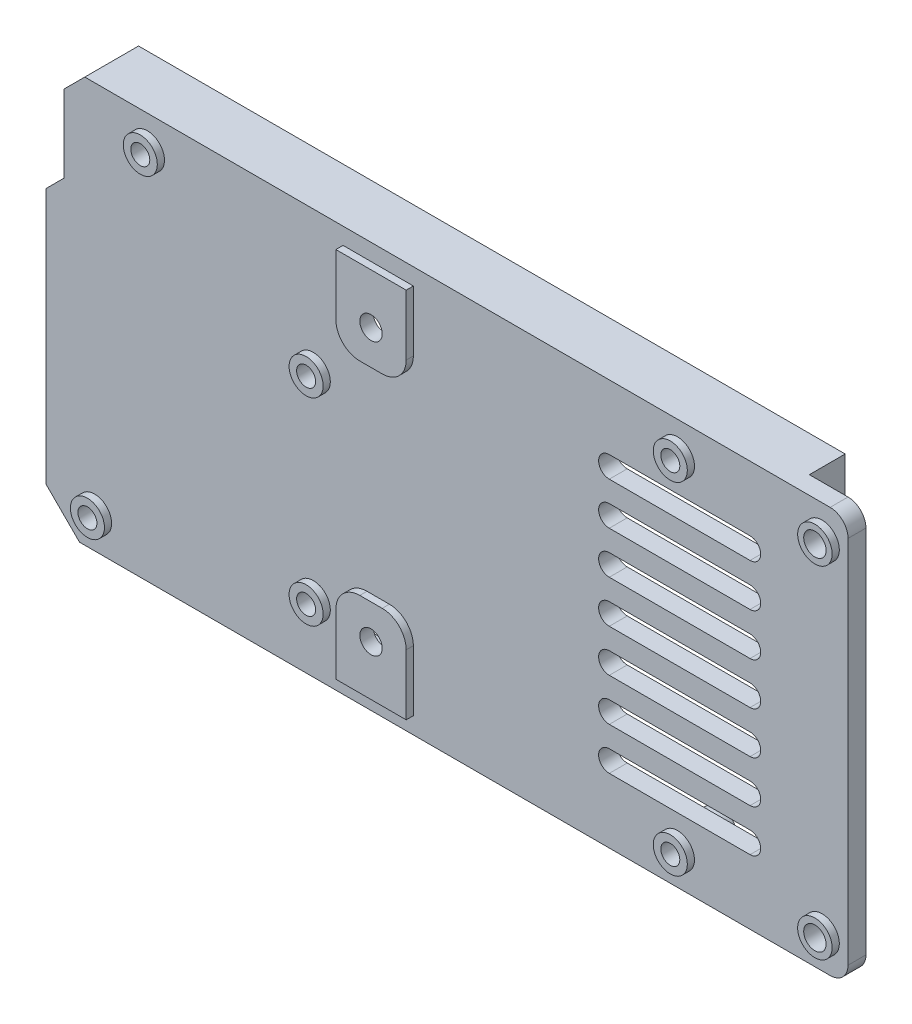
SolidWorks part; units mm, degrees
material "ABS PC"
ref_plane "Front Plane" through (0, 0, 0) normal (0, 0, 1) x (1, 0, 0)
ref_plane "Top Plane" through (0, 0, 0) normal (0, 1, 0) x (1, 0, 0)
ref_plane "Right Plane" through (0, 0, 0) normal (1, 0, 0) x (0, 0, -1)
sketch "Sketch1" plane through (0, 0, -0.0381) normal (0, 0, 1) x (1, 0, 0)
  line L24 (-48.26, 14.0081) -> (-50.8, 11.4681)
  line L25 (-50.8, 11.4681) -> (-50.8, -23.1521)
  line L26 (-50.8, -23.1521) -> (-47.244, -26.7081)
  line L27 (-47.244, -26.7081) -> (49.276, -26.7081)
  line L28 (49.276, -26.7081) -> (50.8, -25.1841)
  line L29 (50.8, -25.1841) -> (50.8, 25.1841)
  line L30 (50.8, 25.1841) -> (49.276, 26.7081)
  line L31 (49.276, 26.7081) -> (-46.4966, 26.7081)
  line L32 (-46.4966, 26.7081) -> (-48.26, 24.9447)
  line L33 (-48.26, 24.9447) -> (-48.26, 14.0081)
  circle A8 centre (36.6776, -24.1681) radius 1.5621
  circle A9 centre (-45.9486, -24.1681) radius 1.5621
  circle A10 centre (-14.9479, -19.2896) radius 1.5621
  circle A11 centre (-38.4556, 24.1681) radius 1.5621
  circle A12 centre (-14.9479, 8.7266) radius 1.3153
  circle A13 centre (36.6776, 24.1681) radius 1.5621
  dimension "D1" = 2.6305
  dimension "D2" = 3.1242
  dimension "D3" = 36.6776
  dimension "D4" = 49.276
  dimension "D5" = 50.8
  dimension "D6" = 14.9479
  dimension "D7" = 38.4556
  dimension "D8" = 45.9486
  dimension "D9" = 46.4966
  dimension "D10" = 47.244
  dimension "D11" = 48.26
  dimension "D12" = 50.8
  dimension "D13" = 8.7266
  dimension "D14" = 11.4681
  dimension "D15" = 24.9447
  dimension "D16" = 24.1681
  dimension "D17" = 23.1521
  dimension "D20" = 19.2896
  dimension "D22" = 24.1681
sketch "Sketch2" plane through (0, 0, 0) normal (0, 0, 1) x (1, 0, 0)
  line L0 (49.276, 26.7081) -> (-46.4966, 26.7081) construction
  line L1 (-46.4966, 26.7081) -> (-48.26, 24.9447) construction
  line L2 (-48.26, 24.9447) -> (-48.26, 14.0081) construction
  line L3 (-48.26, 14.0081) -> (-50.8, 11.4681) construction
  line L4 (-50.8, 11.4681) -> (-50.8, -23.1521) construction
  line L5 (-50.8, -23.1521) -> (-47.244, -26.7081) construction
  line L6 (-47.244, -26.7081) -> (49.276, -26.7081) construction
  line L8 (50.8, -25.1841) -> (50.8, 25.1841) construction
  line L10 (50.8, 26.7081) -> (-46.4966, 26.7081)
  line L11 (-46.4966, 26.7081) -> (-48.26, 24.9447)
  line L12 (-48.26, 24.9447) -> (-48.26, 14.0081)
  line L13 (-48.26, 14.0081) -> (-50.8, 11.4681)
  line L14 (-50.8, 11.4681) -> (-50.8, -23.1521)
  line L15 (-50.8, -23.1521) -> (-47.244, -26.7081)
  line L16 (-47.244, -26.7081) -> (50.8, -26.7081)
  line L18 (50.8, -26.7081) -> (50.8, 26.7081)
  line L20 (52.832, 28.7401) -> (-47.3382, 28.7401)
  line L21 (-47.3382, 28.7401) -> (-50.292, 25.7863)
  line L22 (-50.292, 25.7863) -> (-50.292, 14.8498)
  line L23 (-50.292, 14.8498) -> (-52.832, 12.3098)
  line L24 (-52.832, 12.3098) -> (-52.832, -23.9938)
  line L25 (-52.832, -23.9938) -> (-48.0857, -28.7401)
  line L26 (-48.0857, -28.7401) -> (52.832, -28.7401)
  line L28 (52.832, -28.7401) -> (52.832, 28.7401)
  line L30 (49.276, -26.7081) -> (50.8, -25.1841) construction
  line L31 (50.1177, -28.7401) -> (52.832, -26.0258) construction
  line L32 (52.832, 26.0258) -> (50.1177, 28.7401) construction
  line L33 (50.8, 25.1841) -> (49.276, 26.7081) construction
  line L34 (50.8, -25.1841) -> (50.8, 25.1841) construction
  line L35 (49.276, 26.7081) -> (-46.4966, 26.7081) construction
  line L36 (50.1177, 28.7401) -> (-47.3382, 28.7401) construction
  line L37 (52.832, -26.0258) -> (52.832, 26.0258) construction
  line L38 (-47.244, -26.7081) -> (49.276, -26.7081) construction
  line L39 (-48.0857, -28.7401) -> (50.1177, -28.7401) construction
  dimension "D1" = 2.032
extrude "Boss-Extrude2" add sketch "Sketch2" along normal blind 5.08
sketch "Sketch3" plane through (0, 0, 5.08) normal (0, 0, 1) x (1, 0, 0)
  line L0 (-48.0857, -28.7401) -> (52.832, -28.7401) construction
  line L1 (-52.832, -23.9938) -> (-48.0857, -28.7401) construction
  line L2 (-52.832, 12.3098) -> (-52.832, -23.9938) construction
  line L3 (-50.292, 14.8498) -> (-52.832, 12.3098) construction
  line L4 (-50.292, 25.7863) -> (-50.292, 14.8498) construction
  line L5 (-47.3382, 28.7401) -> (-50.292, 25.7863) construction
  line L6 (52.832, 28.7401) -> (-47.3382, 28.7401) construction
  line L7 (-48.0857, -28.7401) -> (60.8584, -28.7401)
  line L8 (-52.832, -23.9938) -> (-48.0857, -28.7401)
  line L9 (-52.832, 12.3098) -> (-52.832, -23.9938)
  line L10 (-50.292, 14.8498) -> (-52.832, 12.3098)
  line L11 (-50.292, 25.7863) -> (-50.292, 14.8498)
  line L12 (-47.3382, 28.7401) -> (-50.292, 25.7863)
  line L13 (60.8584, 28.7401) -> (-47.3382, 28.7401)
  line L14 (60.8584, 28.7401) -> (60.8584, -28.7401)
  circle A0 centre (57.1754, 24.1681) radius 1.5875
  circle A1 centre (57.1754, -24.1681) radius 1.5875
  circle A2 centre (36.6776, 24.1681) radius 1.3462
  circle A3 centre (-38.4556, 24.1681) radius 1.3462
  circle A4 centre (-14.9479, 8.7266) radius 1.3462
  circle A5 centre (-14.9479, -19.2896) radius 1.3462
  circle A6 centre (-45.9486, -24.1681) radius 1.3462
  circle A7 centre (36.6776, -24.1681) radius 1.3462
  point P32 (0, 0)
  point P33 (0, 0)
  point P34 (0, 0)
  dimension "D2" = 2.6924
  dimension "D3" = 3.175
  dimension "D1" = 113.6904
  dimension "D4" = 3.683
extrude "Boss-Extrude3" add sketch "Sketch3" along normal blind 2.54
sketch "Sketch4" plane through (0, 0, 5.08) normal (0, 0, -1) x (-1, 0, 0)
  line L0 (-39.0906, 24.1681) -> (-39.0906, 26.7081)
  line L1 (-50.8, 26.7081) -> (46.4966, 26.7081) construction
  line L2 (-39.0906, 26.7081) -> (-34.2646, 26.7081)
  line L3 (-34.2646, 26.7081) -> (-34.2646, 24.1681)
  line L4 (36.0426, 24.1681) -> (36.0426, 26.7081)
  line L5 (36.0426, 26.7081) -> (40.8686, 26.7081)
  line L6 (-50.8, 26.7081) -> (46.4966, 26.7081) construction
  line L7 (40.8686, 26.7081) -> (40.8686, 24.1681)
  line L8 (48.3616, -24.1681) -> (49.784, -24.1681)
  line L9 (50.8, -23.1521) -> (47.244, -26.7081) construction
  line L10 (49.784, -24.1681) -> (47.244, -26.7081)
  line L11 (47.244, -26.7081) -> (43.5356, -26.7081)
  line L12 (47.244, -26.7081) -> (-50.8, -26.7081) construction
  line L13 (43.5356, -26.7081) -> (43.5356, -24.1681)
  line L14 (-39.0906, -24.1681) -> (-39.0906, -26.7081)
  line L15 (-39.0906, -26.7081) -> (-34.2646, -26.7081)
  line L16 (47.244, -26.7081) -> (-50.8, -26.7081) construction
  line L17 (-34.2646, -26.7081) -> (-34.2646, -24.1681)
  arc A0 (36.0426, 24.1681) -> (40.8686, 24.1681) centre (38.4556, 24.1681) ccw
  circle A1 centre (14.9479, 8.7266) radius 2.413
  circle A2 centre (14.9479, -19.2896) radius 2.413
  arc A3 (48.3616, -24.1681) -> (43.5356, -24.1681) centre (45.9486, -24.1681) ccw
  arc A4 (-34.2646, -24.1681) -> (-39.0906, -24.1681) centre (-36.6776, -24.1681) ccw
  arc A5 (-39.0906, 24.1681) -> (-34.2646, 24.1681) centre (-36.6776, 24.1681) ccw
  circle A6 centre (45.9486, -24.1681) radius 1.3462 construction
  circle A7 centre (14.9479, -19.2896) radius 1.3462 construction
  circle A8 centre (-36.6776, -24.1681) radius 1.3462 construction
  circle A9 centre (14.9479, 8.7266) radius 1.3462 construction
  circle A10 centre (38.4556, 24.1681) radius 1.3462 construction
  circle A11 centre (-36.6776, 24.1681) radius 1.3462 construction
  circle A12 centre (45.9486, -24.1681) radius 1.3462
  circle A13 centre (14.9479, -19.2896) radius 1.3462
  circle A14 centre (-36.6776, -24.1681) radius 1.3462
  circle A15 centre (14.9479, 8.7266) radius 1.3462
  circle A16 centre (38.4556, 24.1681) radius 1.3462
  circle A17 centre (-36.6776, 24.1681) radius 1.3462
  dimension "D1" = 4.826
  dimension "D2" = 4.826
extrude "Boss-Extrude4" add sketch "Sketch4" along normal blind 3.4671
sketch "Sketch5" plane through (0, 0, 5.08) normal (0, 0, -1) x (-1, 0, 0)
  line L0 (-46.9646, 18.0594) -> (-27.0129, 18.0594) construction
  line L1 (-46.9646, 19.5707) -> (-27.0129, 19.5707)
  line L2 (-46.9646, 16.5481) -> (-27.0129, 16.5481)
  line L3 (-50.8, -26.7081) -> (-50.8, 26.7081) construction
  line L4 (-50.8, 26.7081) -> (46.4966, 26.7081) construction
  line L5 (-46.9646, 12.0396) -> (-27.0129, 12.0396) construction
  line L6 (-46.9646, 13.5509) -> (-27.0129, 13.5509)
  line L7 (-46.9646, 10.5283) -> (-27.0129, 10.5283)
  line L8 (-46.9646, 6.0198) -> (-27.0129, 6.0198) construction
  line L9 (-46.9646, 7.5311) -> (-27.0129, 7.5311)
  line L10 (-46.9646, 4.5085) -> (-27.0129, 4.5085)
  line L11 (-46.9646, 0) -> (-27.0129, 0) construction
  line L12 (-46.9646, 1.5113) -> (-27.0129, 1.5113)
  line L13 (-46.9646, -1.5113) -> (-27.0129, -1.5113)
  line L14 (-46.9646, -6.0198) -> (-27.0129, -6.0198) construction
  line L15 (-46.9646, -4.5085) -> (-27.0129, -4.5085)
  line L16 (-46.9646, -7.5311) -> (-27.0129, -7.5311)
  line L17 (-46.9646, -12.0396) -> (-27.0129, -12.0396) construction
  line L18 (-46.9646, -10.5283) -> (-27.0129, -10.5283)
  line L19 (-46.9646, -13.5509) -> (-27.0129, -13.5509)
  line L20 (-46.9646, -18.0594) -> (-27.0129, -18.0594) construction
  line L21 (-46.9646, -16.5481) -> (-27.0129, -16.5481)
  line L22 (-46.9646, -19.5707) -> (-27.0129, -19.5707)
  line L23 (47.244, -26.7081) -> (-50.8, -26.7081) construction
  arc A0 (-46.9646, 19.5707) -> (-46.9646, 16.5481) centre (-46.9646, 18.0594) ccw
  arc A1 (-27.0129, 16.5481) -> (-27.0129, 19.5707) centre (-27.0129, 18.0594) ccw
  arc A2 (-46.9646, 13.5509) -> (-46.9646, 10.5283) centre (-46.9646, 12.0396) ccw
  arc A3 (-27.0129, 10.5283) -> (-27.0129, 13.5509) centre (-27.0129, 12.0396) ccw
  arc A4 (-46.9646, 7.5311) -> (-46.9646, 4.5085) centre (-46.9646, 6.0198) ccw
  arc A5 (-27.0129, 4.5085) -> (-27.0129, 7.5311) centre (-27.0129, 6.0198) ccw
  arc A6 (-46.9646, 1.5113) -> (-46.9646, -1.5113) centre (-46.9646, 0) ccw
  arc A7 (-27.0129, -1.5113) -> (-27.0129, 1.5113) centre (-27.0129, 0) ccw
  arc A8 (-46.9646, -4.5085) -> (-46.9646, -7.5311) centre (-46.9646, -6.0198) ccw
  arc A9 (-27.0129, -7.5311) -> (-27.0129, -4.5085) centre (-27.0129, -6.0198) ccw
  arc A10 (-46.9646, -10.5283) -> (-46.9646, -13.5509) centre (-46.9646, -12.0396) ccw
  arc A11 (-27.0129, -13.5509) -> (-27.0129, -10.5283) centre (-27.0129, -12.0396) ccw
  arc A12 (-46.9646, -16.5481) -> (-46.9646, -19.5707) centre (-46.9646, -18.0594) ccw
  arc A13 (-27.0129, -19.5707) -> (-27.0129, -16.5481) centre (-27.0129, -18.0594) ccw
  point P2 (-36.9887, 18.0594)
  point P7 (-48.4759, 18.0594)
  point P8 (-25.5016, 18.0594)
  point P16 (-36.9887, 12.0396)
  point P23 (-36.9887, 6.0198)
  point P30 (-36.9887, 0)
  point P37 (-36.9887, -6.0198)
  point P44 (-36.9887, -12.0396)
  point P51 (-36.9887, -18.0594)
  dimension "D1" = 3.0226
  dimension "D2" = 22.9743
  dimension "D3" = 25.2984
  dimension "D4" = 10.16
  dimension "D6" = 10.16
  dimension "D5" = 7
extrude "Cut-Extrude1" cut sketch "Sketch5" against normal up to next
sketch "Sketch6" plane through (0, 0, 7.62) normal (0, 0, 1) x (1, 0, 0)
  line L0 (-7.3343, -14.3891) -> (-4.1593, -14.3891)
  line L1 (-0.762, -17.7864) -> (-0.762, -26.3779)
  line L2 (-0.762, -26.3779) -> (-10.7315, -26.3779)
  line L3 (-10.7315, -26.3779) -> (-10.7315, -17.7864)
  line L4 (-52.832, 12.3098) -> (-52.832, -23.9938) construction
  line L5 (-48.0857, -28.7401) -> (60.8584, -28.7401) construction
  line L6 (-5.7468, -14.3891) -> (-5.7468, -22.939) construction
  line L7 (0, 0) -> (-25.6269, 0) construction
  line L8 (-5.7468, 14.3891) -> (-5.7468, 22.939) construction
  line L9 (-10.7315, 26.3779) -> (-10.7315, 17.7864)
  line L10 (-0.762, 26.3779) -> (-10.7315, 26.3779)
  line L11 (-0.762, 17.7864) -> (-0.762, 26.3779)
  line L12 (-7.3343, 14.3891) -> (-4.1593, 14.3891)
  circle A0 centre (-14.9479, -19.2896) radius 2.413 construction
  circle A1 centre (-14.9479, 8.7266) radius 2.413 construction
  circle A2 centre (57.1754, -24.1681) radius 1.5875 construction
  circle A3 centre (57.1754, 24.1681) radius 1.5875 construction
  circle A4 centre (36.6776, -24.1681) radius 1.3462 construction
  circle A5 centre (36.6776, 24.1681) radius 1.3462 construction
  circle A6 centre (-14.9479, -19.2896) radius 1.3462 construction
  circle A7 centre (-14.9479, 8.7266) radius 1.3462 construction
  circle A8 centre (-38.4556, 24.1681) radius 1.3462 construction
  circle A9 centre (-45.9486, -24.1681) radius 1.3462 construction
  circle A10 centre (-14.9479, -19.2896) radius 2.413
  circle A11 centre (-14.9479, 8.7266) radius 2.413
  circle A12 centre (57.1754, -24.1681) radius 1.5875
  circle A13 centre (57.1754, 24.1681) radius 1.5875
  circle A14 centre (36.6776, -24.1681) radius 1.3462
  circle A15 centre (36.6776, 24.1681) radius 1.3462
  circle A16 centre (-14.9479, -19.2896) radius 1.3462
  circle A17 centre (-14.9479, 8.7266) radius 1.3462
  circle A18 centre (-38.4556, 24.1681) radius 1.3462
  circle A19 centre (-45.9486, -24.1681) radius 1.3462
  circle A20 centre (-45.9486, -24.1681) radius 2.413
  circle A21 centre (-38.4556, 24.1681) radius 2.413
  circle A22 centre (36.6776, 24.1681) radius 2.413
  circle A23 centre (36.6776, -24.1681) radius 2.413
  circle A24 centre (57.1754, 24.1681) radius 2.4448
  circle A25 centre (57.1754, -24.1681) radius 2.4448
  arc A26 (-4.1593, -14.3891) -> (-0.762, -17.7864) centre (-4.1593, -17.7864) cw
  arc A27 (-10.7315, -17.7864) -> (-7.3343, -14.3891) centre (-7.3343, -17.7864) cw
  circle A28 centre (-5.7468, -19.2896) radius 1.5875
  circle A29 centre (-5.7468, 19.2896) radius 1.5875
  arc A30 (-10.7315, 17.7864) -> (-7.3343, 14.3891) centre (-7.3343, 17.7864) ccw
  arc A31 (-4.1593, 14.3891) -> (-0.762, 17.7864) centre (-4.1593, 17.7864) ccw
  dimension "D1" = 4.8895
  dimension "D2" = 11.9888
  dimension "D4" = 3.175
  dimension "D3" = 9.9695
  dimension "D5" = 52.07
  dimension "D6" = 14.351
extrude "Boss-Extrude5" add sketch "Sketch6" along normal blind 1.016
sketch "Sketch8" plane through (0, 0, 5.08) normal (0, 0, -1) x (-1, 0, 0)
  line L8 (9.8425, 17.7864) -> (9.8425, 25.4889)
  line L9 (4.1593, 15.2781) -> (7.3343, 15.2781)
  line L10 (1.651, 25.4889) -> (1.651, 17.7864)
  line L11 (9.8425, 25.4889) -> (1.651, 25.4889)
  line L12 (9.8425, 17.7864) -> (9.8425, 25.4889)
  line L13 (4.1593, 15.2781) -> (7.3343, 15.2781)
  line L14 (1.651, 25.4889) -> (1.651, 17.7864)
  line L15 (9.8425, 25.4889) -> (1.651, 25.4889)
  line L20 (1.651, -25.4889) -> (9.8425, -25.4889)
  line L21 (1.651, -17.7864) -> (1.651, -25.4889)
  line L22 (7.3343, -15.2781) -> (4.1593, -15.2781)
  line L23 (9.8425, -25.4889) -> (9.8425, -17.7864)
  line L24 (1.651, -25.4889) -> (9.8425, -25.4889)
  line L25 (1.651, -17.7864) -> (1.651, -25.4889)
  line L26 (7.3343, -15.2781) -> (4.1593, -15.2781)
  line L27 (9.8425, -25.4889) -> (9.8425, -17.7864)
  arc A4 (7.3343, 15.2781) -> (9.8425, 17.7864) centre (7.3343, 17.7864) ccw
  arc A5 (1.651, 17.7864) -> (4.1593, 15.2781) centre (4.1593, 17.7864) ccw
  arc A6 (7.3343, 15.2781) -> (9.8425, 17.7864) centre (7.3343, 17.7864) ccw
  arc A7 (1.651, 17.7864) -> (4.1593, 15.2781) centre (4.1593, 17.7864) ccw
  arc A10 (4.1593, -15.2781) -> (1.651, -17.7864) centre (4.1593, -17.7864) ccw
  arc A11 (9.8425, -17.7864) -> (7.3343, -15.2781) centre (7.3343, -17.7864) ccw
  arc A12 (4.1593, -15.2781) -> (1.651, -17.7864) centre (4.1593, -17.7864) ccw
  arc A13 (9.8425, -17.7864) -> (7.3343, -15.2781) centre (7.3343, -17.7864) ccw
  dimension "D1" = 0.889
  dimension "D2" = 0.889
extrude "Cut-Extrude2" cut sketch "Sketch8" against normal blind 1.6383
sketch "Sketch9" plane through (0, 0, 6.7183) normal (0, 0, -1) x (-1, 0, 0)
  circle A0 centre (5.7468, -19.2896) radius 1.5875 construction
  circle A1 centre (5.7468, 19.2896) radius 1.5875 construction
  circle A2 centre (5.7468, -19.2896) radius 1.5875
  circle A3 centre (5.7468, 19.2896) radius 1.5875
extrude "Cut-Extrude3" cut sketch "Sketch9" against normal up to next
fillet "Fillet1" radius 2.54 2 edges at (60.8584, 28.7401, 6.35) (60.8584, -28.7401, 6.35)
